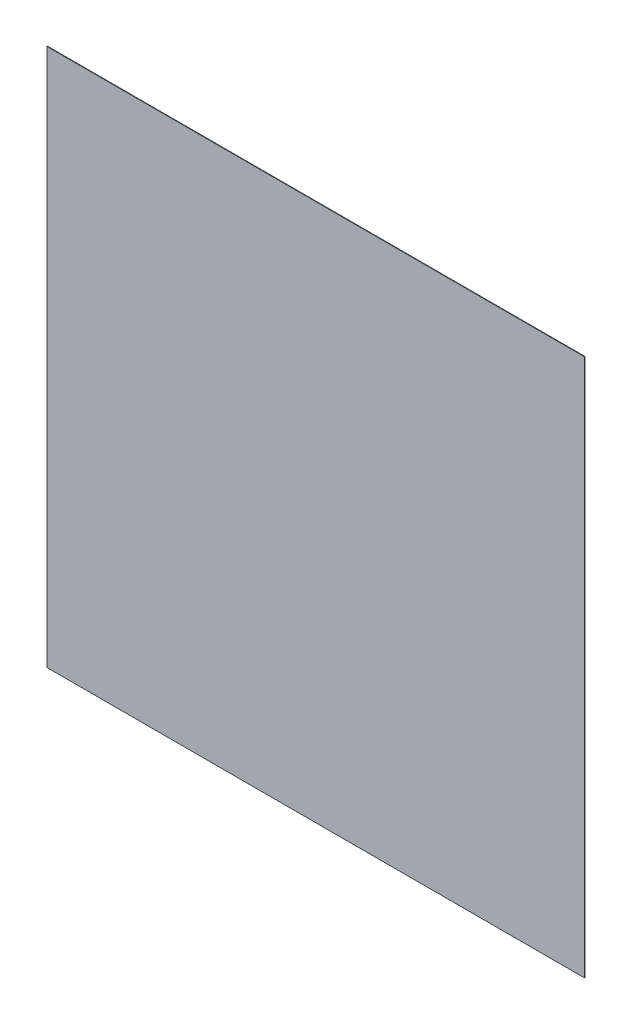
SolidWorks part; units mm, degrees
ref_plane "Front Plane" through (0, 0, 0) normal (1, 0, 0) x (0, 1, 0)
ref_plane "Top Plane" through (0, 0, 0) normal (0, 0, 1) x (0, 1, 0)
ref_plane "Right Plane" through (0, 0, 0) normal (0, 1, 0) x (-1, 0, 0)
sketch "Sketch1" plane through (0, 0, 0) normal (0, 0, 1) x (0, 1, 0)
  line L1 (-1270, -1270) -> (1270, -1270)
  line L2 (-1270, -1270) -> (-1270, 1270)
  line L3 (-1270, 1270) -> (1270, 1270)
  line L4 (1270, -1270) -> (1270, 1270)
  line L5 (-1270, -1270) -> (1270, 1270) construction
  line L6 (-1270, 1270) -> (1270, -1270) construction
  point P0 (0, 0)
  dimension "D1" = 2540
  dimension "D2" = 2540
extrude "Boss-Extrude1" add sketch "Sketch1" along normal blind 2.54
